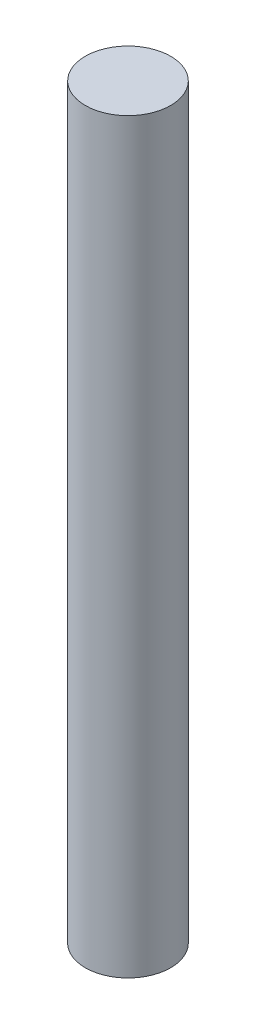
SolidWorks part; units mm, degrees
ref_plane "前视基准面" through (0, 0, 0) normal (0, 0, 1) x (1, 0, 0)
ref_plane "上视基准面" through (0, 0, 0) normal (0, 1, 0) x (1, 0, 0)
ref_plane "右视基准面" through (0, 0, 0) normal (1, 0, 0) x (0, 0, -1)
other "Configuration Table"
sketch "草图1" plane through (0, 0, 0) normal (0, 1, 0) x (1, 0, 0)
  circle A0 centre (0, 0) radius 4
  dimension "D1" = 8
extrude "凸台-拉伸1" add sketch "草图1" along normal blind 70
